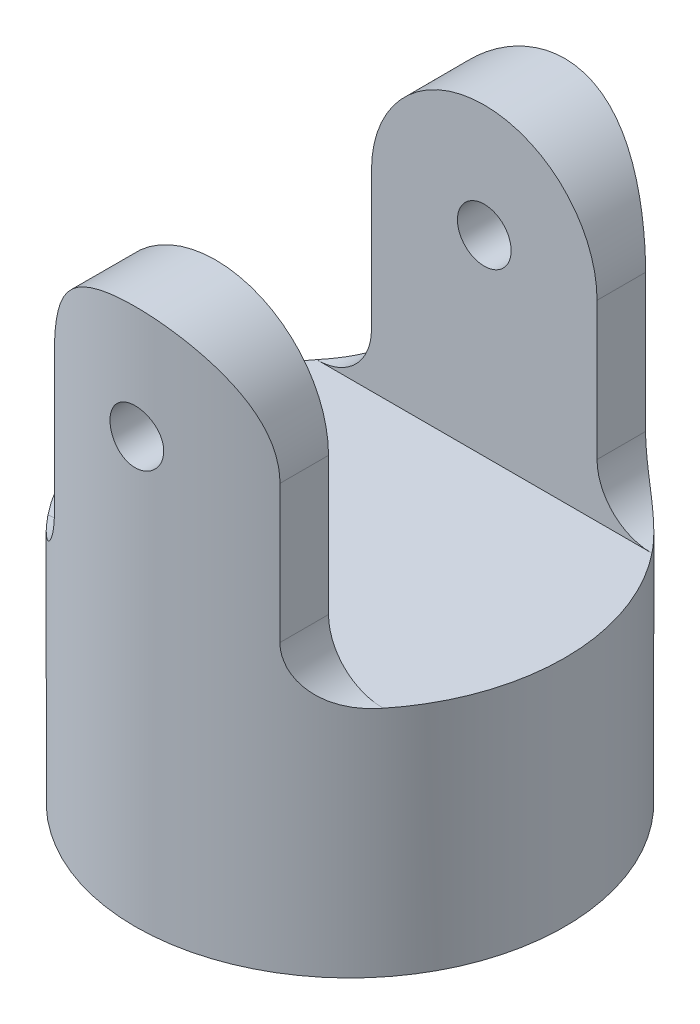
SolidWorks part; units mm, degrees
ref_plane "Front Plane" through (0, 0, 0) normal (0, 0, 1) x (1, 0, 0)
ref_plane "Top Plane" through (0, 0, 0) normal (0, 1, 0) x (1, 0, 0)
ref_plane "Right Plane" through (0, 0, 0) normal (1, 0, 0) x (0, 0, -1)
sketch "Sketch1" plane through (0, 0, 0) normal (0, 1, 0) x (1, 0, 0)
  circle A0 centre (0, 0) radius 6
  dimension "D1" = 12
extrude "Boss-Extrude1" add sketch "Sketch1" along normal blind 15
sketch "Sketch2" plane through (0, 0, 0) normal (1, 0, 0) x (0, 0, -1)
  line L0 (6, 15) -> (-6, 15) construction
  line L1 (-3.75, 15) -> (3.75, 15)
  line L2 (-3.75, 15) -> (-3.75, 6.5)
  line L3 (-3.75, 6.5) -> (3.75, 6.5)
  line L4 (3.75, 15) -> (3.75, 6.5)
  line L5 (-6, 0) -> (6, 0) construction
  point P8 (0, 6.5)
  dimension "D1" = 6.5
  dimension "D2" = 7.5
extrude "Cut-Extrude1" cut sketch "Sketch2" against normal through all both and the other way through all contours L2 L1 L4 L3
sketch "Sketch3" plane through (0, 0, 0) normal (0, 0, 1) x (1, 0, 0)
  line L0 (4.6837, 15) -> (-4.6837, 15) construction
  line L1 (-3.15, 11.85) -> (-3.15, 8)
  line L2 (-4.65, 6.5) -> (-4.6837, 6.5)
  line L3 (-4.6837, 15) -> (-4.6837, 6.5) construction
  line L4 (4.6837, 15) -> (-4.6837, 15)
  line L5 (-4.6837, 15) -> (-4.6837, 6.5)
  line L7 (0, -6.6) -> (0, 6.6) construction
  line L8 (4.6837, 15) -> (4.6837, 6.5)
  line L9 (4.65, 6.5) -> (4.6837, 6.5)
  line L10 (3.15, 11.85) -> (3.15, 8)
  arc A0 (3.15, 11.85) -> (-3.15, 11.85) centre (0, 11.85) ccw
  arc A1 (-3.15, 8) -> (-4.65, 6.5) centre (-4.65, 8) cw
  arc A2 (3.15, 8) -> (4.65, 6.5) centre (4.65, 8) ccw
  circle A3 centre (0, 11.85) radius 0.75
  dimension "D1" = 6.3
  dimension "D2" = 1.5
  dimension "D3" = 1.5
extrude "Cut-Extrude2" cut sketch "Sketch3" against normal through all both and the other way through all contours A1 L1 A0 L4 L5 L2 | L10 A2 L9 L8 L4 A0 | A3
